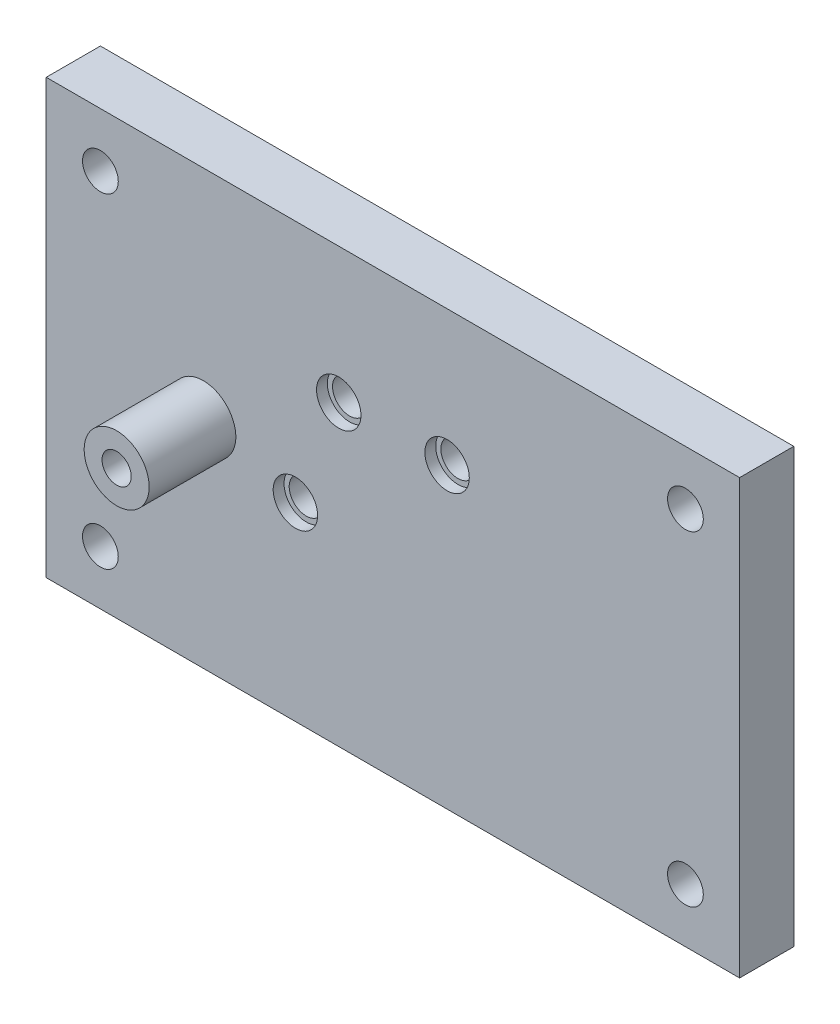
SolidWorks part; units mm, degrees
ref_plane "Front Plane" through (0, 0, 0) normal (0, 0, 1) x (1, 0, 0)
ref_plane "Top Plane" through (0, 0, 0) normal (0, 1, 0) x (1, 0, 0)
ref_plane "Right Plane" through (0, 0, 0) normal (1, 0, 0) x (0, 0, -1)
other "Configuration Table"
sketch "Sketch2" plane through (0, 0, 0) normal (0, 0, 1) x (1, 0, 0)
  line L1 (-64, -40) -> (64, -40)
  line L2 (-64, -40) -> (-64, 40)
  line L3 (-64, 40) -> (64, 40)
  line L4 (64, -40) -> (64, 40)
extrude "Base_plate" add sketch "Sketch2" along normal blind 10 from offset 0
sketch "Sketch3" plane through (0, 0, 0) normal (0, 0, 1) x (1, 0, 0)
  circle A0 centre (-35, 0) radius 6
extrude "Pivot_pedestal" add sketch "Sketch3" along normal blind 16 from offset 10
sketch "Sketch4" plane through (0, 0, 0) normal (0, 0, 1) x (1, 0, 0)
  circle A0 centre (-35, 0) radius 2.7
extrude "Pivot_clearance" cut sketch "Sketch4" along normal blind 26 from offset 0
sketch "Sketch5" plane through (0, 0, 0) normal (0, 0, 1) x (1, 0, 0)
  circle A0 centre (-10, 15) radius 3.15
extrude "Locator_clearance" cut sketch "Sketch5" along normal blind 10 from offset 0
sketch "Sketch6" plane through (0, 0, 0) normal (0, 0, 1) x (1, 0, 0)
  circle A0 centre (10, 15) radius 3.15
extrude "Cut-Extrude3" cut sketch "Sketch6" along normal blind 10 from offset 0
sketch "Sketch7" plane through (0, 0, 0) normal (0, 0, 1) x (1, 0, 0)
  circle A0 centre (-18, -5) radius 3.15
extrude "Side_locator_clearance" cut sketch "Sketch7" along normal blind 10 from offset 0
sketch "Sketch8" plane through (0, 0, 0) normal (0, 0, 1) x (1, 0, 0)
  circle A0 centre (-10, 15) radius 4.1
extrude "Locator_shoulder_counterbore" cut sketch "Sketch8" along normal blind 2 from offset 8
sketch "Sketch9" plane through (0, 0, 0) normal (0, 0, 1) x (1, 0, 0)
  circle A0 centre (10, 15) radius 4.1
extrude "Cut-Extrude6" cut sketch "Sketch9" along normal blind 2 from offset 8
sketch "Sketch10" plane through (0, 0, 0) normal (0, 0, 1) x (1, 0, 0)
  circle A0 centre (-18, -5) radius 4.1
extrude "Side_shoulder_counterbore" cut sketch "Sketch10" along normal blind 2 from offset 8
sketch "Sketch11" plane through (0, 0, 0) normal (0, 0, 1) x (1, 0, 0)
  circle A0 centre (-54, -30) radius 3.3
extrude "Bench_mount_M6_clearance" cut sketch "Sketch11" along normal blind 10 from offset 0
sketch "Sketch12" plane through (0, 0, 0) normal (0, 0, 1) x (1, 0, 0)
  circle A0 centre (-54, 30) radius 3.3
extrude "Cut-Extrude9" cut sketch "Sketch12" along normal blind 10 from offset 0
sketch "Sketch13" plane through (0, 0, 0) normal (0, 0, 1) x (1, 0, 0)
  circle A0 centre (54, -30) radius 3.3
extrude "Cut-Extrude10" cut sketch "Sketch13" along normal blind 10 from offset 0
sketch "Sketch14" plane through (0, 0, 0) normal (0, 0, 1) x (1, 0, 0)
  circle A0 centre (54, 30) radius 3.3
extrude "Cut-Extrude11" cut sketch "Sketch14" along normal blind 10 from offset 0
